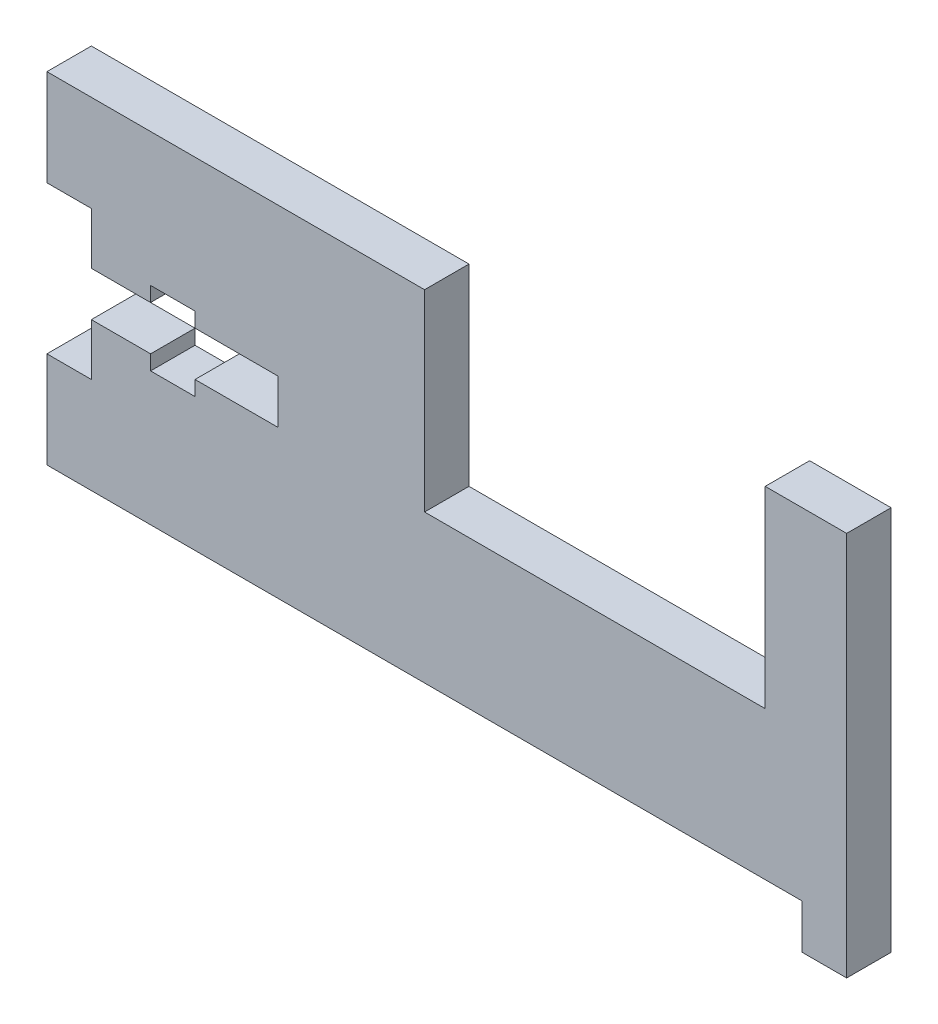
SolidWorks part; units mm, degrees
ref_plane "前视基准面" through (0, 0, 0) normal (0, 0, 1) x (1, 0, 0)
ref_plane "上视基准面" through (0, 0, 0) normal (0, 1, 0) x (1, 0, 0)
ref_plane "右视基准面" through (0, 0, 0) normal (1, 0, 0) x (0, 0, -1)
other "Configuration Table"
sketch "草图1" plane through (0, 0, 0) normal (0, 0, 1) x (1, 0, 0)
  line L0 (0, 0) -> (0, -26)
  line L1 (0, -26) -> (-3, -26)
  line L2 (-3, -26) -> (-3, -23)
  line L3 (-3, -23) -> (-54, -23)
  line L4 (-54, -23) -> (-54, -16.5)
  line L5 (-54, -16.5) -> (-51, -16.5)
  line L6 (-51, -16.5) -> (-51, -13)
  line L7 (-51, -13) -> (-47, -13)
  line L8 (-47, -13) -> (-47, -14)
  line L9 (-47, -14) -> (-44, -14)
  line L10 (-44, -14) -> (-44, -13)
  line L11 (-44, -13) -> (-38.4, -13)
  line L12 (-38.4, -13) -> (-38.4, -10)
  line L13 (-38.4, -10) -> (-44, -10)
  line L14 (-44, -10) -> (-44, -9)
  line L15 (-44, -9) -> (-47, -9)
  line L16 (-47, -9) -> (-47, -10)
  line L17 (-47, -10) -> (-51, -10)
  line L18 (-51, -10) -> (-51, -6.5)
  line L19 (-51, -6.5) -> (-54, -6.5)
  line L20 (-54, -6.5) -> (-54, 0)
  line L21 (-54, 0) -> (-28.5, 0)
  line L22 (-28.5, 0) -> (-28.5, -13)
  line L23 (-28.5, -13) -> (-5.5, -13)
  line L24 (-5.5, -13) -> (-5.5, 0)
  line L25 (-5.5, 0) -> (0, 0)
  dimension "D9" = 1
  dimension "D1" = 26
  dimension "D2" = 3
  dimension "D3" = 3
  dimension "D4" = 51
  dimension "D5" = 6.5
  dimension "D6" = 3
  dimension "D7" = 3.5
  dimension "D8" = 4
  dimension "D10" = 3
  dimension "D11" = 1
  dimension "D12" = 5.6
  dimension "D13" = 3
  dimension "D14" = 1
  dimension "D15" = 3.5
  dimension "D16" = 6.5
  dimension "D17" = 25.5
  dimension "D18" = 13
  dimension "D19" = 23
  dimension "D20" = 13
extrude "凸台-拉伸1" add sketch "草图1" along normal blind 3
